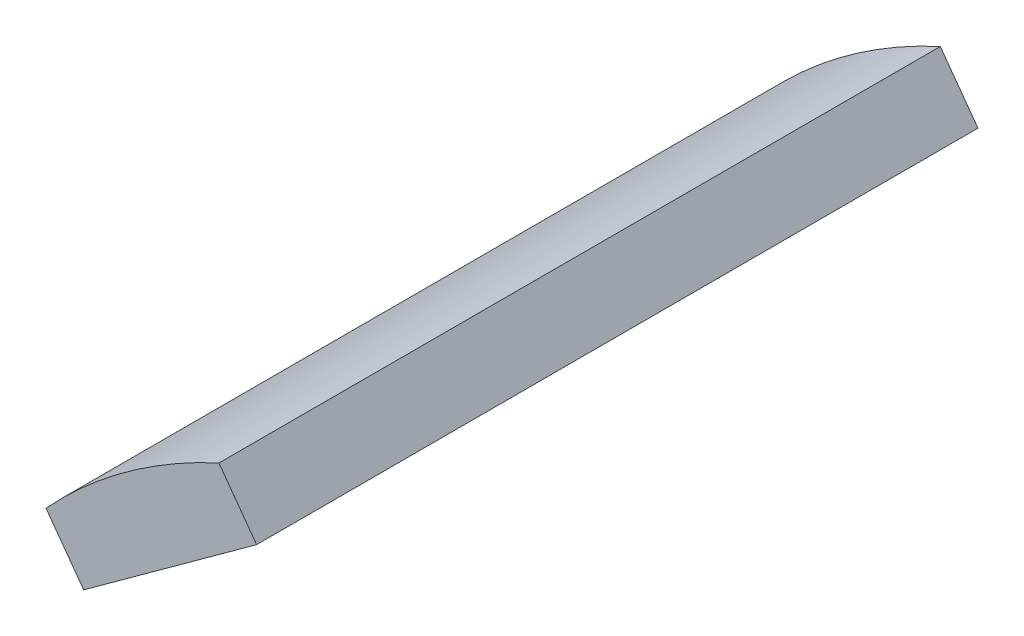
SolidWorks part; units mm, degrees
ref_plane "Ön Düzlem" through (0, 0, 0) normal (0, 0, 1) x (1, 0, 0)
ref_plane "Üst Düzlem" through (0, 0, 0) normal (0, 1, 0) x (1, 0, 0)
ref_plane "Sağ Düzlem" through (0, 0, 0) normal (1, 0, 0) x (0, 0, -1)
sketch "Sketch1" plane through (0, 0, 0) normal (0, 0, 1) x (1, 0, 0)
  line L0 (0, 0) -> (0, 81.5)
  line L1 (10, 81.5) -> (-10, 81.5)
  line L2 (-10, 81.5) -> (-10, 87.5)
  line L3 (10, 81.5) -> (10, 87.5)
  line L4 (15.6743, 80.6013) -> (17.5284, 86.3076)
  line L5 (34.6955, 74.4209) -> (36.5496, 80.1273)
  line L6 (34.6955, 74.4209) -> (15.6743, 80.6013)
  line L7 (39.8143, 71.8127) -> (43.341, 76.6668)
  line L8 (55.9947, 60.057) -> (59.5214, 64.9111)
  line L9 (55.9947, 60.057) -> (39.8143, 71.8127)
  line L10 (60.057, 55.9947) -> (64.9111, 59.5214)
  line L11 (71.8127, 39.8143) -> (76.6668, 43.341)
  line L12 (71.8127, 39.8143) -> (60.057, 55.9947)
  line L13 (74.4209, 34.6955) -> (80.1273, 36.5496)
  line L14 (80.6013, 15.6743) -> (86.3076, 17.5284)
  line L15 (80.6013, 15.6743) -> (74.4209, 34.6955)
  line L16 (81.5, 10) -> (87.5, 10)
  line L17 (81.5, -10) -> (87.5, -10)
  line L18 (81.5, -10) -> (81.5, 10)
  line L19 (80.6013, -15.6743) -> (86.3076, -17.5284)
  line L20 (74.4209, -34.6955) -> (80.1273, -36.5496)
  line L21 (74.4209, -34.6955) -> (80.6013, -15.6743)
  line L22 (71.8127, -39.8143) -> (76.6668, -43.341)
  line L23 (60.057, -55.9947) -> (64.9111, -59.5214)
  line L24 (60.057, -55.9947) -> (71.8127, -39.8143)
  line L25 (55.9947, -60.057) -> (59.5214, -64.9111)
  line L26 (39.8143, -71.8127) -> (43.341, -76.6668)
  line L27 (39.8143, -71.8127) -> (55.9947, -60.057)
  line L28 (34.6955, -74.4209) -> (36.5496, -80.1273)
  line L29 (15.6743, -80.6013) -> (17.5284, -86.3076)
  line L30 (15.6743, -80.6013) -> (34.6955, -74.4209)
  line L31 (10, -81.5) -> (10, -87.5)
  line L32 (-10, -81.5) -> (-10, -87.5)
  line L33 (-10, -81.5) -> (10, -81.5)
  line L34 (-15.6743, -80.6013) -> (-17.5284, -86.3076)
  line L35 (-34.6955, -74.4209) -> (-36.5496, -80.1273)
  line L36 (-34.6955, -74.4209) -> (-15.6743, -80.6013)
  line L37 (-39.8143, -71.8127) -> (-43.341, -76.6668)
  line L38 (-55.9947, -60.057) -> (-59.5214, -64.9111)
  line L39 (-55.9947, -60.057) -> (-39.8143, -71.8127)
  line L40 (-60.057, -55.9947) -> (-64.9111, -59.5214)
  line L41 (-71.8127, -39.8143) -> (-76.6668, -43.341)
  line L42 (-71.8127, -39.8143) -> (-60.057, -55.9947)
  line L43 (-74.4209, -34.6955) -> (-80.1273, -36.5496)
  line L44 (-80.6013, -15.6743) -> (-86.3076, -17.5284)
  line L45 (-80.6013, -15.6743) -> (-74.4209, -34.6955)
  line L46 (-81.5, -10) -> (-87.5, -10)
  line L47 (-81.5, 10) -> (-87.5, 10)
  line L48 (-81.5, 10) -> (-81.5, -10)
  line L49 (-80.6013, 15.6743) -> (-86.3076, 17.5284)
  line L50 (-74.4209, 34.6955) -> (-80.1273, 36.5496)
  line L51 (-74.4209, 34.6955) -> (-80.6013, 15.6743)
  line L52 (-71.8127, 39.8143) -> (-76.6668, 43.341)
  line L53 (-60.057, 55.9947) -> (-64.9111, 59.5214)
  line L54 (-60.057, 55.9947) -> (-71.8127, 39.8143)
  line L55 (-55.9947, 60.057) -> (-59.5214, 64.9111)
  line L56 (-39.8143, 71.8127) -> (-43.341, 76.6668)
  line L57 (-39.8143, 71.8127) -> (-55.9947, 60.057)
  line L58 (-34.6955, 74.4209) -> (-36.5496, 80.1273)
  line L59 (-15.6743, 80.6013) -> (-17.5284, 86.3076)
  line L60 (-15.6743, 80.6013) -> (-34.6955, 74.4209)
  line L61 (34.6955, 74.4209) -> (34.7846, 74.3755)
  line L62 (35.1494, 75.3119) -> (40.2683, 72.7037) construction
  line L63 (39.7252, 71.8581) -> (39.8143, 71.8127)
  line L64 (35.2385, 75.2665) -> (40.1792, 72.7491)
  line L65 (34.7846, 74.3755) -> (35.2385, 75.2665)
  line L66 (55.9947, 60.057) -> (56.0654, 59.9863)
  line L67 (39.7252, 71.8581) -> (40.1792, 72.7491)
  line L68 (34.7846, 74.3755) -> (35.1931, 75.1774) construction
  line L69 (39.7252, 71.8581) -> (40.1338, 72.66) construction
  line L70 (35.1931, 75.1774) -> (40.1338, 72.66) construction
  line L71 (34.6955, 74.4209) -> (35.1494, 75.3119) construction
  line L72 (39.8143, 71.8127) -> (40.2683, 72.7037) construction
  line L73 (56.0654, 59.9863) -> (56.7725, 60.6934)
  line L74 (56.7725, 60.6934) -> (60.6934, 56.7725)
  line L75 (59.9863, 56.0654) -> (60.6934, 56.7725)
  line L76 (59.9863, 56.0654) -> (60.057, 55.9947)
  line L77 (71.8127, 39.8143) -> (71.8581, 39.7252)
  line L78 (71.8581, 39.7252) -> (72.7491, 40.1792)
  line L79 (72.7491, 40.1792) -> (75.2665, 35.2385)
  line L80 (74.3755, 34.7846) -> (75.2665, 35.2385)
  line L81 (74.3755, 34.7846) -> (74.4209, 34.6955)
  line L82 (80.6013, 15.6743) -> (80.6169, 15.5756)
  line L83 (80.6169, 15.5756) -> (81.6046, 15.732)
  line L84 (81.6046, 15.732) -> (82.472, 10.2552)
  line L85 (81.4844, 10.0988) -> (82.472, 10.2552)
  line L86 (81.4844, 10.0988) -> (81.5, 10)
  line L87 (81.5, -10) -> (81.4844, -10.0988)
  line L88 (81.4844, -10.0988) -> (82.472, -10.2552)
  line L89 (82.472, -10.2552) -> (81.6046, -15.732)
  line L90 (80.6169, -15.5756) -> (81.6046, -15.732)
  line L91 (80.6169, -15.5756) -> (80.6013, -15.6743)
  line L92 (74.4209, -34.6955) -> (74.3755, -34.7846)
  line L93 (74.3755, -34.7846) -> (75.2665, -35.2385)
  line L94 (75.2665, -35.2385) -> (72.7491, -40.1792)
  line L95 (71.8581, -39.7252) -> (72.7491, -40.1792)
  line L96 (71.8581, -39.7252) -> (71.8127, -39.8143)
  line L97 (60.057, -55.9947) -> (59.9863, -56.0654)
  line L98 (59.9863, -56.0654) -> (60.6934, -56.7725)
  line L99 (60.6934, -56.7725) -> (56.7725, -60.6934)
  line L100 (56.0654, -59.9863) -> (56.7725, -60.6934)
  line L101 (56.0654, -59.9863) -> (55.9947, -60.057)
  line L102 (39.8143, -71.8127) -> (39.7252, -71.8581)
  line L103 (39.7252, -71.8581) -> (40.1792, -72.7491)
  line L104 (40.1792, -72.7491) -> (35.2385, -75.2665)
  line L105 (34.7846, -74.3755) -> (35.2385, -75.2665)
  line L106 (34.7846, -74.3755) -> (34.6955, -74.4209)
  line L107 (15.6743, -80.6013) -> (15.5756, -80.6169)
  line L108 (15.5756, -80.6169) -> (15.732, -81.6046)
  line L109 (15.732, -81.6046) -> (10.2552, -82.472)
  line L110 (10.0988, -81.4844) -> (10.2552, -82.472)
  line L111 (10.0988, -81.4844) -> (10, -81.5)
  line L112 (-10, -81.5) -> (-10.0988, -81.4844)
  line L113 (-10.0988, -81.4844) -> (-10.2552, -82.472)
  line L114 (-10.2552, -82.472) -> (-15.732, -81.6046)
  line L115 (-15.5756, -80.6169) -> (-15.732, -81.6046)
  line L116 (-15.5756, -80.6169) -> (-15.6743, -80.6013)
  line L117 (-34.6955, -74.4209) -> (-34.7846, -74.3755)
  line L118 (-34.7846, -74.3755) -> (-35.2385, -75.2665)
  line L119 (-35.2385, -75.2665) -> (-40.1792, -72.7491)
  line L120 (-39.7252, -71.8581) -> (-40.1792, -72.7491)
  line L121 (-39.7252, -71.8581) -> (-39.8143, -71.8127)
  line L122 (-55.9947, -60.057) -> (-56.0654, -59.9863)
  line L123 (-56.0654, -59.9863) -> (-56.7725, -60.6934)
  line L124 (-56.7725, -60.6934) -> (-60.6934, -56.7725)
  line L125 (-59.9863, -56.0654) -> (-60.6934, -56.7725)
  line L126 (-59.9863, -56.0654) -> (-60.057, -55.9947)
  line L127 (-71.8127, -39.8143) -> (-71.8581, -39.7252)
  line L128 (-71.8581, -39.7252) -> (-72.7491, -40.1792)
  line L129 (-72.7491, -40.1792) -> (-75.2665, -35.2385)
  line L130 (-74.3755, -34.7846) -> (-75.2665, -35.2385)
  line L131 (-74.3755, -34.7846) -> (-74.4209, -34.6955)
  line L132 (-80.6013, -15.6743) -> (-80.6169, -15.5756)
  line L133 (-80.6169, -15.5756) -> (-81.6046, -15.732)
  line L134 (-81.6046, -15.732) -> (-82.472, -10.2552)
  line L135 (-81.4844, -10.0988) -> (-82.472, -10.2552)
  line L136 (-81.4844, -10.0988) -> (-81.5, -10)
  line L137 (-81.5, 10) -> (-81.4844, 10.0988)
  line L138 (-81.4844, 10.0988) -> (-82.472, 10.2552)
  line L139 (-82.472, 10.2552) -> (-81.6046, 15.732)
  line L140 (-80.6169, 15.5756) -> (-81.6046, 15.732)
  line L141 (-80.6169, 15.5756) -> (-80.6013, 15.6743)
  line L142 (-74.4209, 34.6955) -> (-74.3755, 34.7846)
  line L143 (-74.3755, 34.7846) -> (-75.2665, 35.2385)
  line L144 (-75.2665, 35.2385) -> (-72.7491, 40.1792)
  line L145 (-71.8581, 39.7252) -> (-72.7491, 40.1792)
  line L146 (-71.8581, 39.7252) -> (-71.8127, 39.8143)
  line L147 (-60.057, 55.9947) -> (-59.9863, 56.0654)
  line L148 (-59.9863, 56.0654) -> (-60.6934, 56.7725)
  line L149 (-60.6934, 56.7725) -> (-56.7725, 60.6934)
  line L150 (-56.0654, 59.9863) -> (-56.7725, 60.6934)
  line L151 (-56.0654, 59.9863) -> (-55.9947, 60.057)
  line L152 (-39.8143, 71.8127) -> (-39.7252, 71.8581)
  line L153 (-39.7252, 71.8581) -> (-40.1792, 72.7491)
  line L154 (-40.1792, 72.7491) -> (-35.2385, 75.2665)
  line L155 (-34.7846, 74.3755) -> (-35.2385, 75.2665)
  line L156 (-34.7846, 74.3755) -> (-34.6955, 74.4209)
  line L157 (-15.6743, 80.6013) -> (-15.5756, 80.6169)
  line L158 (-15.5756, 80.6169) -> (-15.732, 81.6046)
  line L159 (-15.732, 81.6046) -> (-10.2552, 82.472)
  line L160 (-10.0988, 81.4844) -> (-10.2552, 82.472)
  line L161 (-10.0988, 81.4844) -> (-10, 81.5)
  line L162 (10, 81.5) -> (10.0988, 81.4844)
  line L163 (10.0988, 81.4844) -> (10.2552, 82.472)
  line L164 (10.2552, 82.472) -> (15.732, 81.6046)
  line L165 (15.5756, 80.6169) -> (15.732, 81.6046)
  line L166 (15.5756, 80.6169) -> (15.6743, 80.6013)
  circle A0 centre (0, 0) radius 60
  arc A2 (10, 87.5) -> (-10, 87.5) centre (0, 38) ccw
  arc A3 (36.5496, 80.1273) -> (17.5284, 86.3076) centre (11.7426, 36.1401) ccw
  arc A4 (59.5214, 64.9111) -> (43.341, 76.6668) centre (22.3358, 30.7426) ccw
  arc A5 (76.6668, 43.341) -> (64.9111, 59.5214) centre (30.7426, 22.3358) ccw
  arc A6 (86.3076, 17.5284) -> (80.1273, 36.5496) centre (36.1401, 11.7426) ccw
  arc A7 (87.5, -10) -> (87.5, 10) centre (38, 0) ccw
  arc A8 (80.1273, -36.5496) -> (86.3076, -17.5284) centre (36.1401, -11.7426) ccw
  arc A9 (64.9111, -59.5214) -> (76.6668, -43.341) centre (30.7426, -22.3358) ccw
  arc A10 (43.341, -76.6668) -> (59.5214, -64.9111) centre (22.3358, -30.7426) ccw
  arc A11 (17.5284, -86.3076) -> (36.5496, -80.1273) centre (11.7426, -36.1401) ccw
  arc A12 (-10, -87.5) -> (10, -87.5) centre (0, -38) ccw
  arc A13 (-36.5496, -80.1273) -> (-17.5284, -86.3076) centre (-11.7426, -36.1401) ccw
  arc A14 (-59.5214, -64.9111) -> (-43.341, -76.6668) centre (-22.3358, -30.7426) ccw
  arc A15 (-76.6668, -43.341) -> (-64.9111, -59.5214) centre (-30.7426, -22.3358) ccw
  arc A16 (-86.3076, -17.5284) -> (-80.1273, -36.5496) centre (-36.1401, -11.7426) ccw
  arc A17 (-87.5, 10) -> (-87.5, -10) centre (-38, 0) ccw
  arc A18 (-80.1273, 36.5496) -> (-86.3076, 17.5284) centre (-36.1401, 11.7426) ccw
  arc A19 (-64.9111, 59.5214) -> (-76.6668, 43.341) centre (-30.7426, 22.3358) ccw
  arc A20 (-43.341, 76.6668) -> (-59.5214, 64.9111) centre (-22.3358, 30.7426) ccw
  arc A21 (-17.5284, 86.3076) -> (-36.5496, 80.1273) centre (-11.7426, 36.1401) ccw
  point P7 (0, 81.5)
  point P107 (0, 0)
  point P231 (0, 0)
  dimension "D1" = 81.5
  dimension "D3" = 50.5
  dimension "D2" = 20
  dimension "D4" = 6
  dimension "D5" = 6
  dimension "D7" = 20
  dimension "D6" = 20
extrude "Boss-Extrude2" add sketch "Sketch1" along normal blind 67.5 contours L56 A20 L55 L57
